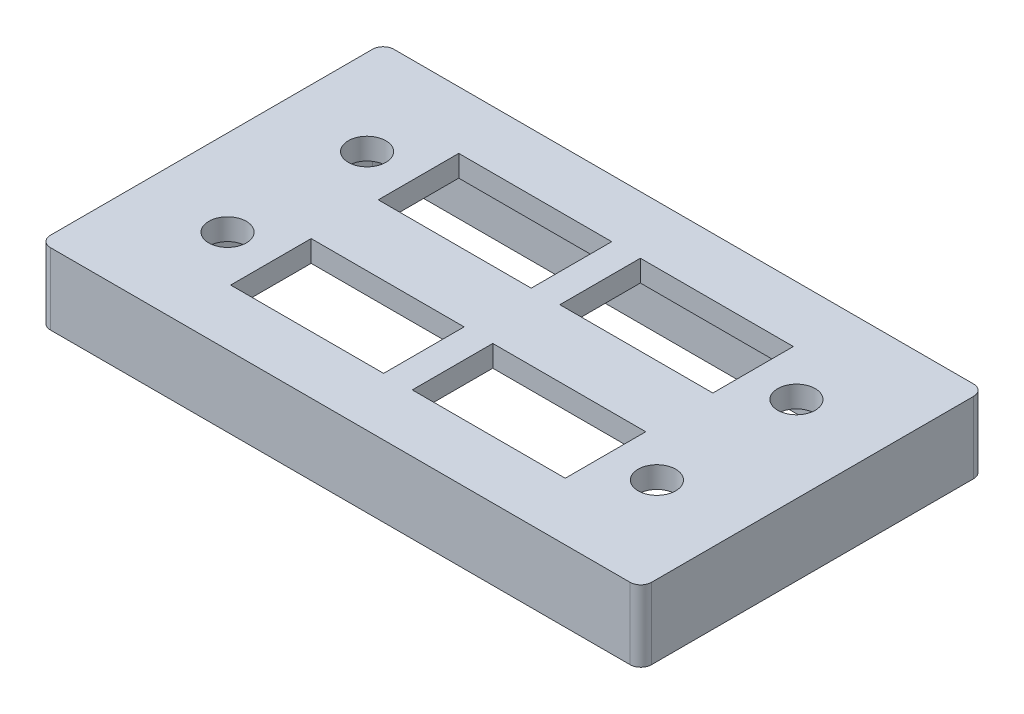
SolidWorks part; units mm, degrees
ref_plane "Front Plane" through (0, 0, 0) normal (0, 0, 1) x (1, 0, 0)
ref_plane "Top Plane" through (0, 0, 0) normal (0, 1, 0) x (1, 0, 0)
ref_plane "Right Plane" through (0, 0, 0) normal (1, 0, 0) x (0, 0, -1)
sketch "Sketch1" plane through (0, 0, 0) normal (0, 1, 0) x (1, 0, 0)
  line L1 (-28, 16) -> (28, 16)
  line L2 (-28, 16) -> (-28, -16)
  line L3 (-28, -16) -> (28, -16)
  line L4 (28, 16) -> (28, -16)
  line L5 (-28, 16) -> (28, -16) construction
  line L6 (-28, -16) -> (28, 16) construction
  point P0 (0, 0)
  dimension "D1" = 56
  dimension "D2" = 32
extrude "Boss-Extrude1" add sketch "Sketch1" along normal blind 2
sketch "Sketch2" plane through (0, 0, 0) normal (0, 1, 0) x (1, 0, 0)
  circle A0 centre (20, 6.5) radius 1.75
  dimension "D1" = 3.5
  dimension "D2" = 20
  dimension "D3" = 6.5
extrude "Cut-Extrude1" cut sketch "Sketch2" along normal through all
mirror "Mirror1" about plane through (0, 0, 0) normal (0, 0, 1) of "Cut-Extrude1"
mirror "Mirror2" about plane through (0, 0, 0) normal (1, 0, 0) of "Mirror1", "Cut-Extrude1"
sketch "Sketch4" plane through (0, 0, 0) normal (0, 1, 0) x (1, 0, 0)
  line L1 (1.335, 3.125) -> (15.585, 3.125)
  line L2 (1.335, 3.125) -> (1.335, 10.625)
  line L3 (1.335, 10.625) -> (15.585, 10.625)
  line L4 (15.585, 3.125) -> (15.585, 10.625)
  point P4 (8.46, 3.125)
  point P6 (1.335, 6.875)
  dimension "D1" = 14.25
  dimension "D2" = 7.5
  dimension "D3" = 8.46
  dimension "D4" = 6.875
extrude "Cut-Extrude2" cut sketch "Sketch4" along normal through all
mirror "Mirror3" about plane through (0, 0, 0) normal (1, 0, 0) of "Cut-Extrude2"
mirror "Mirror4" about plane through (0, 0, 0) normal (0, 0, 1) of "Mirror3", "Cut-Extrude2"
sketch "Sketch5" plane through (0, 0, 0) normal (0, -1, 0) x (1, 0, 0)
  line L4 (28, -16) -> (28, 16)
  line L5 (-28, -16) -> (28, -16)
  line L6 (-28, 16) -> (-28, -16)
  line L7 (28, 16) -> (-28, 16)
  line L8 (28, -16) -> (28, 16)
  line L9 (-28, -16) -> (28, -16)
  line L10 (-28, 16) -> (-28, -16)
  line L11 (28, 16) -> (-28, 16)
  line L16 (25, -13) -> (25, 13)
  line L17 (-25, -13) -> (25, -13)
  line L18 (-25, 13) -> (-25, -13)
  line L19 (25, 13) -> (-25, 13)
  line L20 (25, -13) -> (25, 13)
  line L21 (-25, -13) -> (25, -13)
  line L22 (-25, 13) -> (-25, -13)
  line L23 (25, 13) -> (-25, 13)
  dimension "D1" = 0
  dimension "D2" = 3
extrude "Boss-Extrude2" add sketch "Sketch5" along normal blind 4.65
sketch "Sketch6" plane through (0, -4.65, 0) normal (0, -1, 0) x (1, 0, 0)
  line L0 (25, -13) -> (25, 13) construction
  line L1 (-25, -13) -> (25, -13) construction
  line L2 (-25, 13) -> (-25, -13) construction
  line L3 (25, 13) -> (-25, 13) construction
  line L4 (25, -13) -> (25, 13)
  line L5 (-25, -13) -> (25, -13)
  line L6 (-25, 13) -> (-25, -13)
  line L7 (25, 13) -> (-25, 13)
  line L8 (25.5, -13.5) -> (25.5, 13.5)
  line L9 (25.5, 13.5) -> (-25.5, 13.5)
  line L10 (-25.5, 13.5) -> (-25.5, -13.5)
  line L11 (-25.5, -13.5) -> (25.5, -13.5)
  dimension "D1" = 0.5
extrude "Boss-Extrude3" add sketch "Sketch6" along normal blind 1
fillet "Fillet1" radius 1 12 edges at (28, -1.325, 16) (28, -1.325, -16) (25, -2.825, -13) (25, -2.825, 13) (-28, -1.325, 16) (-25, -2.825, 13) (-25, -2.825, -13) (-28, -1.325, -16) (25.5, -5.15, 13.5) (25.5, -5.15, -13.5) (-25.5, -5.15, 13.5) (-25.5, -5.15, -13.5)
